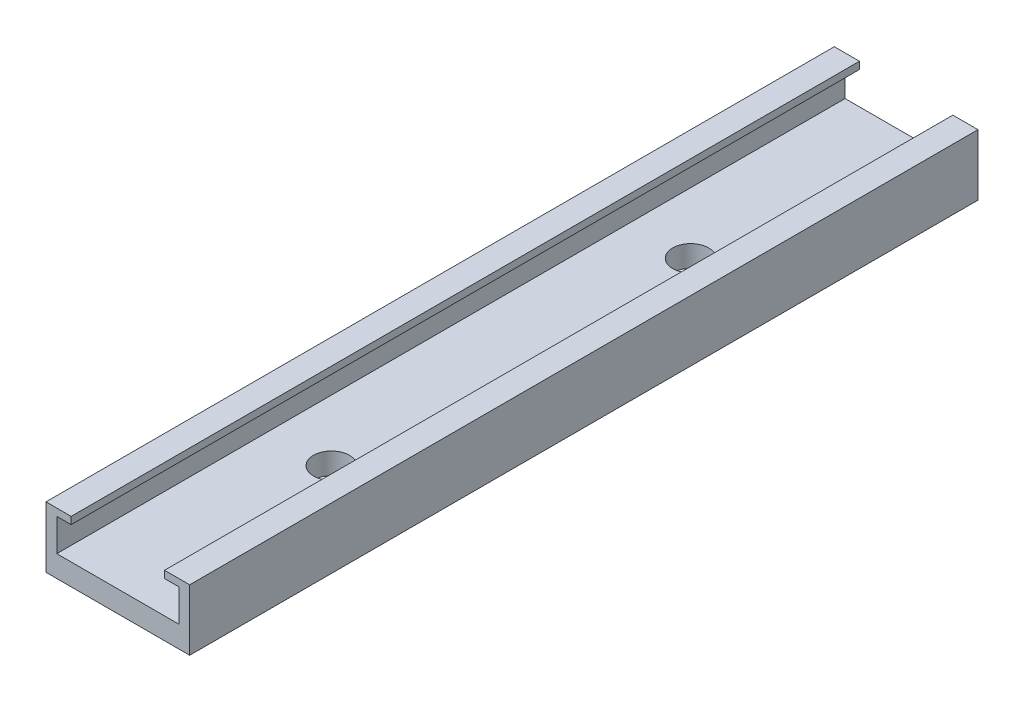
SolidWorks part; units mm, degrees
material "1060 Alloy"
ref_plane "Front Plane" through (0, 0, 0) normal (0, 0, 1) x (1, 0, 0)
ref_plane "Top Plane" through (0, 0, 0) normal (0, 1, 0) x (1, 0, 0)
ref_plane "Right Plane" through (0, 0, 0) normal (1, 0, 0) x (0, 0, -1)
sketch "Sketch1" plane through (0, 0, 0) normal (0, 0, 1) x (1, 0, 0)
  line L0 (-10, 0.3916) -> (-10, -3.5766)
  line L3 (-10, -8.1084) -> (10, -8.1084)
  line L4 (6.5, 0.3916) -> (6.5, -0.6084)
  line L5 (-6.5, 0.3916) -> (-10, 0.3916)
  line L7 (6.5, -0.6084) -> (8.5, -0.6084)
  line L8 (8.5, -0.6084) -> (8.5, -5.1084)
  line L9 (8.5, -5.1084) -> (-8.5, -5.1084)
  line L10 (-8.5, -5.1084) -> (-8.5, -0.6084)
  line L11 (-8.5, -0.6084) -> (-6.5, -0.6084)
  line L12 (-10, -3.5766) -> (-10, -8.1084)
  line L13 (10, 0.3916) -> (10, -8.1084)
  line L14 (10, 0.3916) -> (6.5, 0.3916)
  line L15 (-6.5, -0.6084) -> (-6.5, 0.3916)
  dimension "D1" = 17
  dimension "D2" = 1.5
  dimension "D3" = 20
  dimension "D4" = 3
  dimension "D5" = 2
  dimension "D6" = 2
  dimension "D7" = 1
  dimension "D8" = 1
  dimension "D9" = 4.5
extrude "Boss-Extrude2" add sketch "Sketch1" along normal blind 109.73
sketch "Sketch2" plane through (0, -8.1084, 0) normal (0, -1, 0) x (1, 0, 0)
  circle A0 centre (0, 30) radius 2.5
  circle A1 centre (0, 80) radius 2.5
extrude "Cut-Extrude1" cut sketch "Sketch2" against normal blind 10
